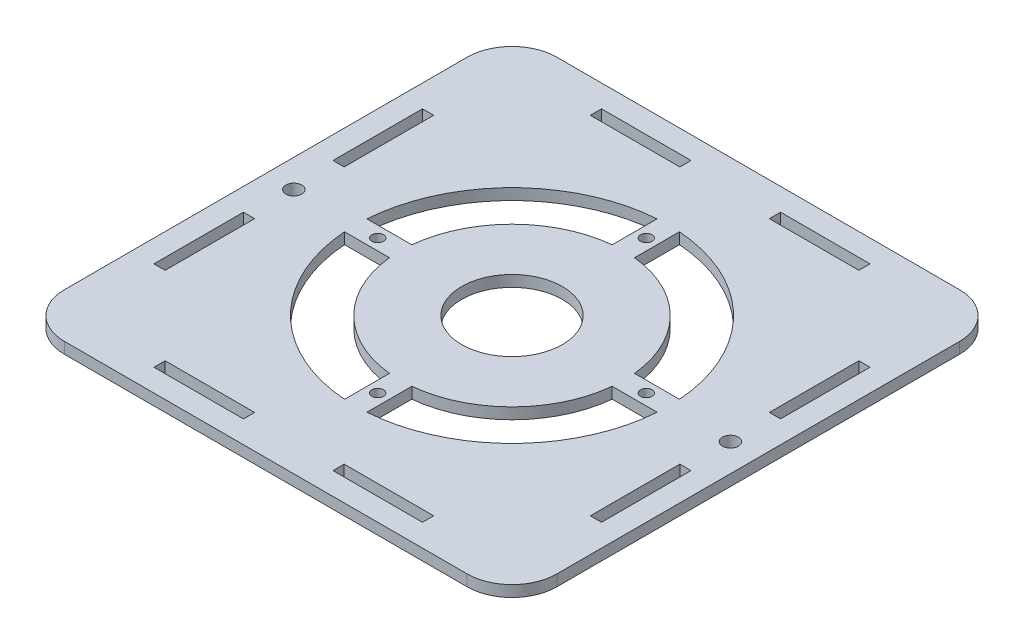
SolidWorks part; units mm, degrees
ref_plane "Front Plane" through (0, 0, 0) normal (0, 0, 1) x (1, 0, 0)
ref_plane "Top Plane" through (0, 0, 0) normal (0, 1, 0) x (1, 0, 0)
ref_plane "Right Plane" through (0, 0, 0) normal (1, 0, 0) x (0, 0, -1)
sketch "Sketch1" plane through (0, 0, 0) normal (0, 1, 0) x (1, 0, 0)
  line L1 (0, 0) -> (139.7, 0)
  line L2 (0, 0) -> (0, 139.7)
  line L3 (0, 139.7) -> (139.7, 139.7)
  line L4 (139.7, 0) -> (139.7, 139.7)
  dimension "D1" = 139.7
  dimension "D2" = 139.7
extrude "Boss-Extrude1" add sketch "Sketch1" along normal blind 3.175
sketch "Sketch13" plane through (0, 3.175, 0) normal (0, 1, 0) x (1, 0, 0)
  line L1 (0, 139.7) -> (0, 0) construction
  line L2 (31.75, 9.525) -> (57.15, 9.525)
  line L3 (31.75, 9.525) -> (31.75, 6.35)
  line L4 (31.75, 6.35) -> (57.15, 6.35)
  line L5 (57.15, 9.525) -> (57.15, 6.35)
  line L6 (31.75, 9.525) -> (57.15, 6.35) construction
  line L7 (31.75, 6.35) -> (57.15, 9.525) construction
  line L8 (0, 0) -> (139.7, 0) construction
  line L9 (82.55, 9.525) -> (107.95, 9.525)
  line L10 (82.55, 9.525) -> (82.55, 6.35)
  line L11 (82.55, 6.35) -> (107.95, 6.35)
  line L12 (107.95, 9.525) -> (107.95, 6.35)
  point P0 (44.45, 7.9375)
  dimension "D1" = 31.75
  dimension "D2" = 3.175
  dimension "D4" = 6.35
  dimension "D5" = 2
  dimension "D3" = 25.4
extrude "Cut-Extrude6" cut sketch "Sketch13" against normal blind 6.35
pattern_linear "LPattern7" count 2 spacing 123.825 along (0, 0, -1) of "Cut-Extrude6"
sketch "Sketch14" plane through (0, 3.175, 0) normal (0, 1, 0) x (1, 0, 0)
  line L0 (0, 139.7) -> (0, 0) construction
  line L1 (6.35, 31.75) -> (9.525, 31.75)
  line L2 (6.35, 31.75) -> (6.35, 57.15)
  line L3 (6.35, 57.15) -> (9.525, 57.15)
  line L4 (9.525, 31.75) -> (9.525, 57.15)
  line L5 (0, 0) -> (139.7, 0) construction
  line L6 (130.175, 57.15) -> (133.35, 57.15)
  line L7 (130.175, 31.75) -> (130.175, 57.15)
  line L8 (133.35, 31.75) -> (133.35, 57.15)
  line L9 (130.175, 31.75) -> (133.35, 31.75)
  line L10 (130.175, 107.95) -> (133.35, 107.95)
  line L11 (130.175, 82.55) -> (130.175, 107.95)
  line L12 (133.35, 82.55) -> (133.35, 107.95)
  line L13 (130.175, 82.55) -> (133.35, 82.55)
  line L14 (6.35, 107.95) -> (9.525, 107.95)
  line L15 (6.35, 82.55) -> (6.35, 107.95)
  line L16 (9.525, 82.55) -> (9.525, 107.95)
  line L17 (6.35, 82.55) -> (9.525, 82.55)
  dimension "D1" = 25.4
  dimension "D2" = 3.175
  dimension "D3" = 6.35
  dimension "D4" = 31.75
  dimension "D5" = 2
  dimension "D6" = 2
extrude "Cut-Extrude7" cut sketch "Sketch14" against normal blind 6.35
hole_wizard "#8 Clearance Hole1" positions "Sketch16" profile "Sketch15" hole size "#8" standard "ANSI Inch"
sketch "Sketch16" plane through (0, 3.175, 0) normal (0, 1, 0) x (1, 0, 0)
  line L0 (9.525, 57.15) -> (6.35, 57.15) construction
  line L1 (6.35, 57.15) -> (6.35, 31.75) construction
  line L4 (130.175, 107.95) -> (130.175, 82.55) construction
  line L5 (133.35, 57.15) -> (130.175, 57.15) construction
  point P0 (7.9375, 69.85)
  point P3 (7.9375, 57.15)
  point P8 (131.826, 69.85)
  point P18 (131.7625, 57.15)
  dimension "D1" = 12.7
  dimension "D2" = 1.5875
  dimension "D3" = 1.651
  dimension "D4" = 12.7
sketch "Sketch15" plane through (7.9375, 3.175, -69.85) normal (1, 0, 0) x (0, 0, 1)
  line L0 (0, 0) -> (0, 11.5107)
  line L1 (0, 11.5107) -> (2.2479, 10.16)
  line L2 (2.2479, 10.16) -> (2.2479, 0)
  line L5 (2.2479, 0) -> (0, 0)
  line L10 (0, 11.5107) -> (-2.2479, 10.16) construction
  line L11 (0, -6.35) -> (0, 107.95) construction
  dimension "Hole Dia." = 4.4958
  dimension "Hole Depth" = 10.16
  dimension "Drill Angle" = 118
sketch "Sketch18" plane through (0, 3.175, 0) normal (0, 1, 0) x (1, 0, 0)
  line L0 (0, 139.7) -> (0, 0) construction
  circle A0 centre (69.85, 69.85) radius 14.2875
  circle A2 centre (7.9375, 69.85) radius 2.2479 construction
  dimension "D1" = 28.575
  dimension "D2" = 69.85
  dimension "D3" = 0
extrude "Cut-Extrude9" cut sketch "Sketch18" against normal blind 7.62
sketch "Sketch19" plane through (0, 3.175, 0) normal (0, 1, 0) x (1, 0, 0)
  line L0 (12.7, 82.55) -> (177.8, 82.55)
  line L3 (9.525, 107.95) -> (6.35, 107.95) construction
  dimension "D1" = 25.4
sketch "Sketch20" plane through (0, 3.175, 0) normal (0, 1, 0) x (1, 0, 0)
  text T0 "Countercat" font "DS-Digital" height in points 72
extrude "Cut-Extrude10" [suppressed] cut sketch "Sketch20" against normal blind 10.16
sketch "Sketch21" plane through (0, 3.175, 0) normal (0, 1, 0) x (1, 0, 0)
  line L0 (12.7, 69.85) -> (63.5, 69.85)
  line L2 (177.8, 69.85) -> (127, 69.85)
  circle A0 centre (69.85, 69.85) radius 14.2875 construction
  dimension "D1" = 50.8
  dimension "D2" = 50.8
  dimension "D3" = 0
  dimension "D4" = 0
sketch "Sketch22" plane through (0, 3.175, 0) normal (0, 1, 0) x (1, 0, 0)
  text T0 "armed" font "DS-Digital" height in points 36
  text T1 "Safe" font "DS-Digital" height in points 36
extrude "Cut-Extrude11" [suppressed] cut sketch "Sketch22" against normal blind 10.16
sketch "Sketch24" plane through (0, 3.175, 0) normal (0, 1, 0) x (1, 0, 0)
  line L0 (6.35, 82.55) -> (9.525, 82.55) construction
  line L2 (33.3375, 87.63) -> (33.3375, 69.85)
  line L4 (40.7602, 81.4016) -> (33.3375, 87.63)
  line L7 (60.325, 87.63) -> (58.7375, 69.85)
  line L8 (52.5256, 80.7677) -> (60.325, 87.63)
  arc A0 (52.5256, 80.7677) -> (40.7602, 81.4016) centre (46.0375, 69.85) ccw
  arc A1 (33.3375, 69.85) -> (58.7375, 69.85) centre (46.0375, 69.85) ccw
  circle A2 centre (7.9375, 69.85) radius 2.2479 construction
  arc A7 (40.7602, 81.4016) -> (39.5537, 80.7702) centre (46.0375, 69.85) ccw
  arc A8 (33.3375, 69.85) -> (34.5363, 75.2364) centre (46.0375, 69.85) cw
  arc A9 (52.5256, 80.7677) -> (54.5658, 79.2605) centre (46.0375, 69.85) cw
  arc A10 (58.7375, 69.85) -> (57.9981, 74.1202) centre (46.0375, 69.85) ccw
  point P1 (7.9375, 82.55)
  dimension "D1" = 25.4
  dimension "D2" = 12.7
  dimension "D3" = 38.1
  dimension "D4" = 50
extrude "Cut-Extrude16" [suppressed] cut sketch "Sketch24" against normal blind 6.35
fillet "Fillet2" [suppressed] radius 0.508
fillet "Fillet6" radius 12.7 4 edges at (139.7, 1.5875, -139.7) (139.7, 1.5875, 0) (0, 1.5875, 0) (0, 1.5875, -139.7)
sketch "Sketch26" plane through (0, 3.175, 0) normal (0, 1, 0) x (1, 0, 0)
  line L1 (66.675, 25.4) -> (73.025, 25.4)
  line L2 (66.675, 25.4) -> (66.675, 114.3)
  line L3 (66.675, 114.3) -> (73.025, 114.3)
  line L4 (73.025, 25.4) -> (73.025, 114.3)
  line L5 (66.675, 25.4) -> (73.025, 114.3) construction
  line L6 (66.675, 114.3) -> (73.025, 25.4) construction
  line L7 (25.5135, 73.025) -> (114.1865, 73.025)
  line L8 (25.5135, 73.025) -> (25.5135, 66.675)
  line L9 (25.5135, 66.675) -> (114.1865, 66.675)
  line L10 (114.1865, 73.025) -> (114.1865, 66.675)
  line L11 (25.5135, 73.025) -> (114.1865, 66.675) construction
  line L12 (25.5135, 66.675) -> (114.1865, 73.025) construction
  circle A0 centre (69.85, 69.85) radius 44.45
  circle A1 centre (69.85, 69.85) radius 31.75
  point P0 (69.85, 69.85)
  dimension "D3" = 63.5
  dimension "D1" = 6.35
  dimension "D2" = 88.9
  dimension "D4" = 6.35
extrude "Cut-Extrude17" cut sketch "Sketch26" against normal blind 7.62 contours A1 L2 A0 L7 | A1 L9 A0 L2 | A1 L4 A0 L9 | A1 L7 A0 L4
hole_wizard "#4 Clearance Hole1" positions "Sketch28" profile "Sketch27" hole size "#4" standard "ANSI Inch"
sketch "Sketch28" plane through (0, 3.175, 0) normal (0, 1, 0) x (1, 0, 0)
  circle A0 centre (69.85, 69.85) radius 14.2875 construction
  point P0 (69.85, 107.95)
  dimension "D1" = 38.1
sketch "Sketch27" plane through (69.85, 3.175, -107.95) normal (1, 0, 0) x (0, 0, 1)
  line L0 (0, 0) -> (0, 11.1406)
  line L1 (0, 11.1406) -> (1.6319, 10.16)
  line L2 (1.6319, 10.16) -> (1.6319, 0)
  line L5 (1.6319, 0) -> (0, 0)
  line L10 (0, 11.1406) -> (-1.6319, 10.16) construction
  line L11 (0, -6.35) -> (0, 107.95) construction
  dimension "Hole Dia." = 3.2639
  dimension "Hole Depth" = 10.16
  dimension "Drill Angle" = 118
pattern_circular "CirPattern1" count 4 every 90 about axis through (69.85, 0, -69.85) along (0, 1, 0) of "#4 Clearance Hole1"
equation "\"THICK\"= .25"
